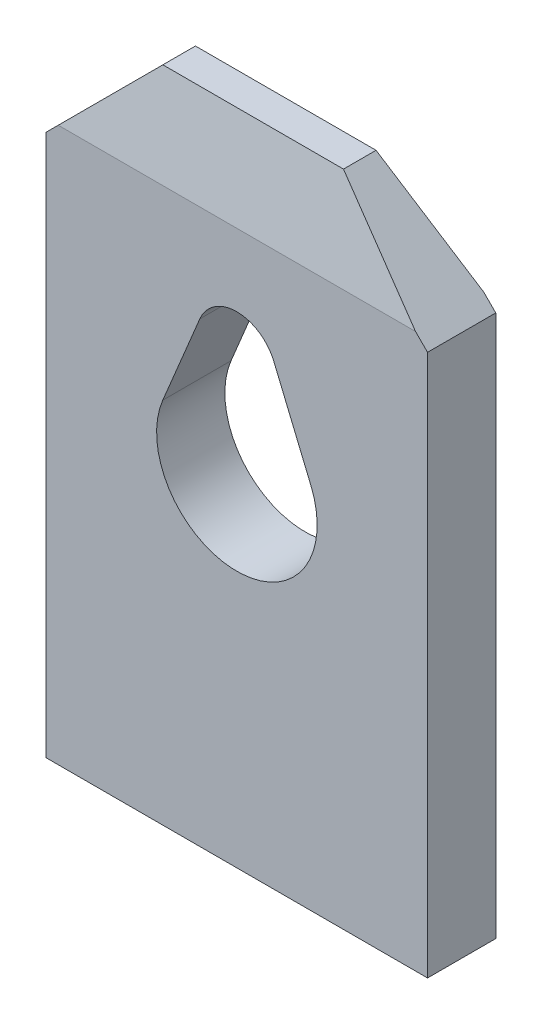
SolidWorks part; units mm, degrees
ref_plane "Front Plane" through (0, 0, 0) normal (0, 0, 1) x (1, 0, 0)
ref_plane "Top Plane" through (0, 0, 0) normal (0, 1, 0) x (1, 0, 0)
ref_plane "Right Plane" through (0, 0, 0) normal (1, 0, 0) x (0, 0, -1)
sketch "Sketch1" plane through (0, 0, 0) normal (1, 0, 0) x (0, 0, -1)
  line L0 (0, 0.15) -> (0, 7.05)
  line L1 (0, 7.05) -> (-0.2414, 8.15)
  line L2 (-0.2414, 8.15) -> (-0.6471, 8.15)
  line L3 (-0.6471, 8.15) -> (-0.85, 7.05)
  line L4 (-0.85, 7.05) -> (-0.85, 0.15)
  line L8 (0, 0.15) -> (-0.85, 0.15)
  point P17 (-0.4443, 8.15)
  dimension "D2" = 0.85
  dimension "D3" = 1.1
  dimension "D9" = 0.6471
  dimension "D10" = 8
extrude "Boss-Extrude1" add sketch "Sketch1" along normal blind 4.75
sketch "Sketch4" plane through (0, 0, 0.85) normal (0, 0, 1) x (1, 0, 0)
  line L0 (0, 6.9) -> (1.25, 8.15)
  line L1 (0, 7.05) -> (0, 0.15) construction
  line L2 (4.75, 8.15) -> (0, 8.15) construction
  line L4 (3.5, 8.15) -> (4.75, 6.9)
  line L5 (4.75, 7.05) -> (4.75, 0.15) construction
  line L6 (0, 6.9) -> (0, 8.15)
  line L7 (0, 8.15) -> (1.25, 8.15)
  line L8 (3.5, 8.15) -> (4.75, 8.15)
  line L9 (4.75, 8.15) -> (4.75, 6.9)
  dimension "D1" = 1.25
  dimension "D2" = 1.25
  dimension "D3" = 1.25
extrude "Cut-Extrude1" cut sketch "Sketch4" against normal up to surface (0.85 mm away) up to face at (2.375, 3.6, 0)
sketch "Sketch5" plane through (0, 0, 0.85) normal (0, 0, 1) x (1, 0, 0)
  line L0 (3.5, 8.15) -> (1.25, 8.15) construction
  line L1 (1.9135, 5.8423) -> (1.4519, 4.7346)
  line L2 (2.8424, 5.8275) -> (3.298, 4.7348)
  line L3 (0, 6.9) -> (0, 0.15) construction
  line L5 (0, 6.9) -> (0, 0.15) construction
  arc A0 (1.4519, 4.7346) -> (3.298, 4.7348) centre (2.375, 4.35) ccw
  arc A1 (2.8424, 5.8275) -> (1.9135, 5.8423) centre (2.375, 5.65) ccw
  dimension "D1" = 2
  dimension "D3" = 1
  dimension "D2" = 3.8
  dimension "D4" = 1.3
  dimension "D5" = 2.8424
  dimension "D7" = 2.375
extrude "Cut-Extrude2" cut sketch "Sketch5" against normal up to surface (0.85 mm away) up to face at (2.375, 4.7, 0)
ref_plane "Plane1" through (0, 0, 0.425) normal (0, 0, 1) x (1, 0, 0)
